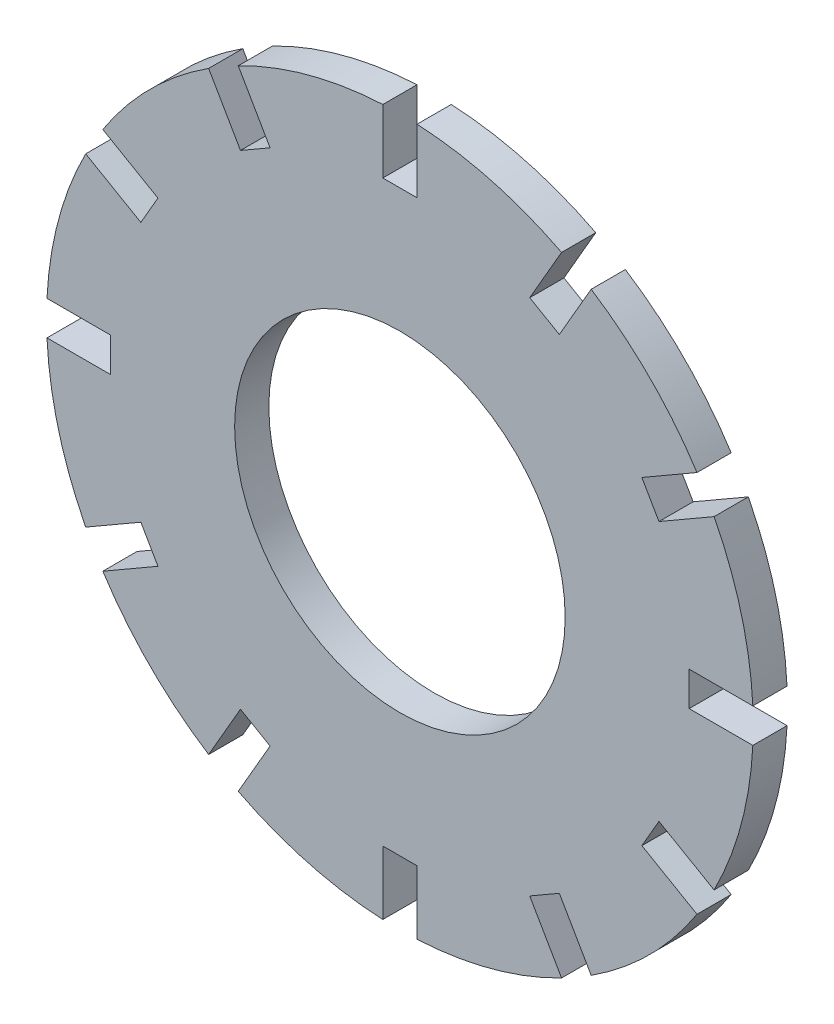
SolidWorks part; units mm, degrees
ref_plane "Alzado" through (0, 0, 0) normal (0, 0, 1) x (1, 0, 0)
ref_plane "Planta" through (0, 0, 0) normal (0, 1, 0) x (1, 0, 0)
ref_plane "Vista lateral" through (0, 0, 0) normal (1, 0, 0) x (0, 0, -1)
sketch "Model" plane through (0, 0, 0) normal (0, 0, 1) x (1, 0, 0)
  line L0 (47.3731, 289.774) -> (50.1663, 294.6119)
  line L1 (47.3731, 289.774) -> (49.9712, 288.274)
  line L2 (49.9712, 288.274) -> (52.7643, 293.1119)
  line L3 (57.211, 281.0343) -> (62.0488, 283.8274)
  line L4 (57.211, 281.0343) -> (58.711, 278.4362)
  line L5 (58.711, 278.4362) -> (63.5488, 281.2293)
  line L6 (61.3609, 268.5465) -> (66.9472, 268.5465)
  line L7 (61.3609, 268.5465) -> (61.3609, 265.5465)
  line L8 (61.3609, 265.5465) -> (66.9472, 265.5465)
  line L9 (58.711, 255.6569) -> (63.5488, 252.8637)
  line L10 (58.711, 255.6569) -> (57.211, 253.0588)
  line L11 (57.211, 253.0588) -> (62.0488, 250.2657)
  line L12 (49.9712, 245.819) -> (52.7643, 240.9812)
  line L13 (49.9712, 245.819) -> (47.3731, 244.319)
  line L14 (47.3731, 244.319) -> (50.1663, 239.4812)
  line L15 (37.4835, 241.6691) -> (37.4835, 236.0828)
  line L16 (37.4835, 241.6691) -> (34.4835, 241.6691)
  line L17 (34.4835, 241.6691) -> (34.4835, 236.0828)
  line L18 (24.5938, 244.319) -> (21.8007, 239.4812)
  line L19 (24.5938, 244.319) -> (21.9957, 245.819)
  line L20 (21.9957, 245.819) -> (19.2026, 240.9812)
  line L21 (14.756, 253.0588) -> (9.9181, 250.2657)
  line L22 (14.756, 253.0588) -> (13.256, 255.6569)
  line L23 (13.256, 255.6569) -> (8.4181, 252.8637)
  line L24 (10.606, 265.5465) -> (5.0198, 265.5465)
  line L25 (10.606, 265.5465) -> (10.606, 268.5465)
  line L26 (10.606, 268.5465) -> (5.0198, 268.5465)
  line L27 (13.256, 278.4362) -> (8.4181, 281.2293)
  line L28 (13.256, 278.4362) -> (14.756, 281.0343)
  line L29 (14.756, 281.0343) -> (9.9181, 283.8274)
  line L30 (21.9957, 288.274) -> (19.2026, 293.1119)
  line L31 (21.9957, 288.274) -> (24.5938, 289.774)
  line L32 (24.5938, 289.774) -> (21.8007, 294.6119)
  line L33 (34.4835, 292.424) -> (34.4835, 298.0102)
  line L34 (34.4835, 292.424) -> (37.4835, 292.424)
  line L35 (37.4835, 292.424) -> (37.4835, 298.0102)
  arc A0 (19.2026, 293.1119) -> (9.9181, 283.8274) centre (35.9835, 267.0465) ccw
  arc A1 (8.4181, 281.2293) -> (5.0198, 268.5465) centre (35.9835, 267.0465) ccw
  arc A2 (5.0198, 265.5465) -> (8.4181, 252.8637) centre (35.9835, 267.0465) ccw
  arc A3 (21.8007, 239.4812) -> (34.4835, 236.0828) centre (35.9835, 267.0465) ccw
  arc A4 (9.9181, 250.2657) -> (19.2026, 240.9812) centre (35.9835, 267.0465) ccw
  arc A5 (37.4835, 236.0828) -> (50.1663, 239.4812) centre (35.9835, 267.0465) ccw
  arc A6 (52.7643, 240.9812) -> (62.0488, 250.2657) centre (35.9835, 267.0465) ccw
  arc A7 (63.5488, 252.8637) -> (66.9472, 265.5465) centre (35.9835, 267.0465) ccw
  arc A8 (66.9472, 268.5465) -> (63.5488, 281.2293) centre (35.9835, 267.0465) ccw
  arc A9 (62.0488, 283.8274) -> (52.7643, 293.1119) centre (35.9835, 267.0465) ccw
  arc A10 (50.1663, 294.6119) -> (37.4835, 298.0102) centre (35.9835, 267.0465) ccw
  arc A11 (34.4835, 298.0102) -> (21.8007, 294.6119) centre (35.9835, 267.0465) ccw
  circle A12 centre (35.9835, 267.0465) radius 14.5
extrude "Saliente-Extruir1" add sketch "Model" along normal blind 3
